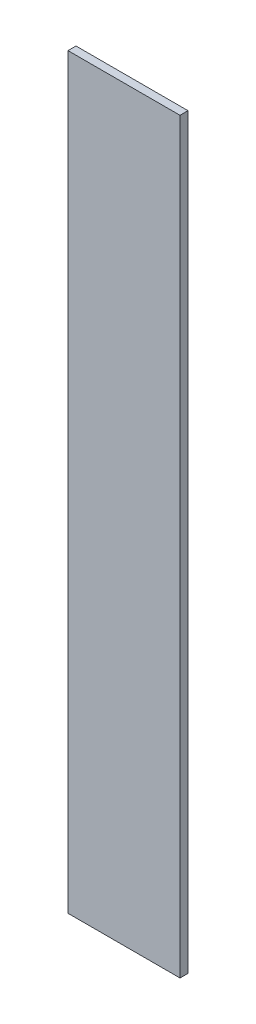
SolidWorks part; units mm, degrees
ref_plane "Front Plane" through (0, 0, 0) normal (1, 0, 0) x (0, 1, 0)
ref_plane "Top Plane" through (0, 0, 0) normal (0, 0, 1) x (0, 1, 0)
ref_plane "Right Plane" through (0, 0, 0) normal (0, 1, 0) x (-1, 0, 0)
sketch "Sketch2" plane through (0, 0, 0) normal (0, 0, 1) x (0, 1, 0)
  line L1 (0, 0) -> (593.09, 0)
  line L2 (0, 0) -> (0, 88.9)
  line L3 (0, 88.9) -> (593.09, 88.9)
  line L4 (593.09, 0) -> (593.09, 88.9)
  dimension "D1" = 88.9
  dimension "D2" = 593.09
extrude "Boss-Extrude1" add sketch "Sketch2" along normal blind 6.35
